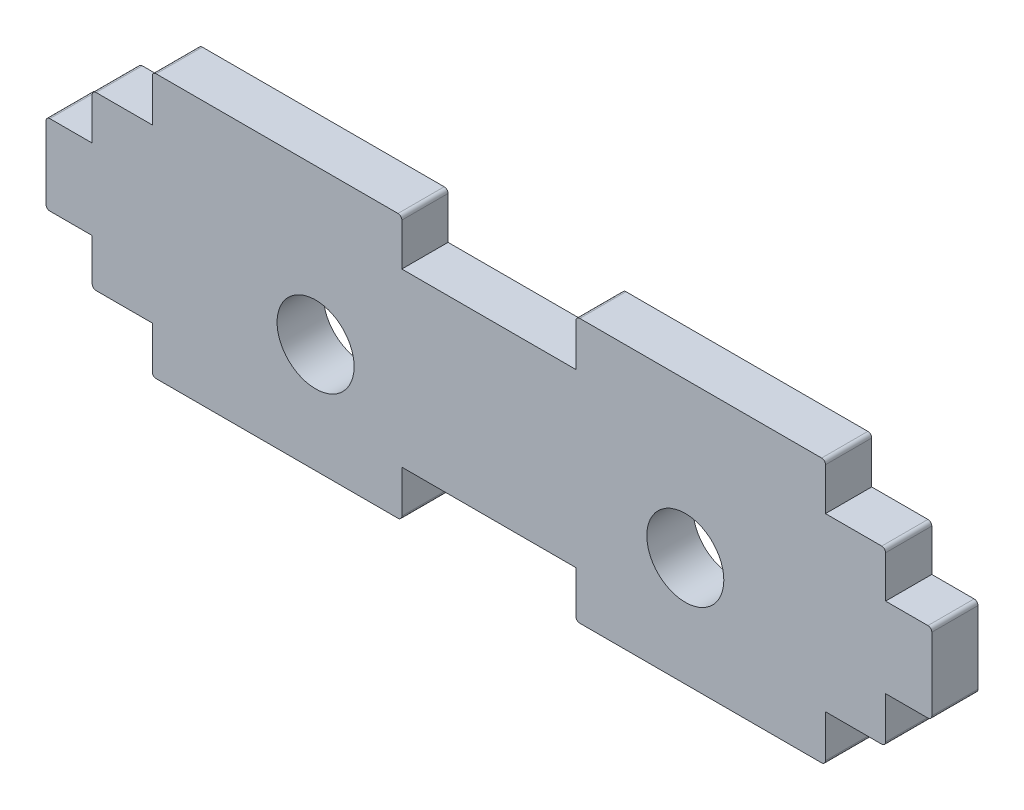
SolidWorks part; units mm, degrees
material "Acrylic (Medium-high impact)"
ref_plane "Front Plane" through (0, 0, 0) normal (0, 0, 1) x (1, 0, 0)
ref_plane "Top Plane" through (0, 0, 0) normal (0, 1, 0) x (1, 0, 0)
ref_plane "Right Plane" through (0, 0, 0) normal (1, 0, 0) x (0, 0, -1)
sketch "Sketch2" plane through (0, 0, 0) normal (0, 0, 1) x (1, 0, 0)
  line L0 (34.25, 2.0562) -> (49.95, 2.0562)
  line L1 (6.75, 2.0562) -> (22.45, 2.0562)
  line L2 (-0.4, 8.275) -> (-0.4, 12.975)
  line L3 (6.75, 19.1937) -> (22.45, 19.1937)
  line L4 (57.1, 8.275) -> (57.1, 12.975)
  line L5 (2.85, 5.0562) -> (6.5, 5.0562)
  line L8 (50.2, 5.0562) -> (53.85, 5.0562)
  line L10 (34.25, 19.1937) -> (49.95, 19.1937)
  line L11 (2.85, 16.1937) -> (6.5, 16.1937)
  line L12 (2.6, 13.225) -> (2.6, 15.9437)
  line L14 (6.5, 2.3062) -> (6.5, 5.0562)
  line L16 (22.7, 2.3062) -> (22.7, 5.0562)
  line L17 (22.7, 5.0562) -> (34, 5.0562)
  line L18 (50.2, 5.0562) -> (50.2, 2.3062)
  line L20 (34, 5.0562) -> (34, 2.3062)
  line L21 (50.2, 16.1937) -> (53.85, 16.1937)
  line L22 (6.5, 16.1937) -> (6.5, 18.9437)
  line L24 (22.7, 16.1937) -> (22.7, 18.9437)
  line L26 (34, 18.9437) -> (34, 16.1937)
  line L27 (-0.15, 13.225) -> (2.6, 13.225)
  line L28 (50.2, 18.9437) -> (50.2, 16.1937)
  line L29 (22.7, 16.1937) -> (34, 16.1937)
  line L31 (-0.15, 8.025) -> (2.6, 8.025)
  line L32 (54.1, 13.225) -> (54.1, 15.9437)
  line L33 (2.6, 8.025) -> (2.6, 5.3062)
  line L34 (56.85, 13.225) -> (54.1, 13.225)
  line L36 (56.85, 8.025) -> (54.1, 8.025)
  line L38 (54.1, 8.025) -> (54.1, 5.3062)
  arc A0 (6.75, 19.1937) -> (6.5, 18.9437) centre (6.75, 18.9437) ccw
  arc A1 (22.7, 18.9437) -> (22.45, 19.1937) centre (22.45, 18.9437) ccw
  arc A2 (34.25, 19.1937) -> (34, 18.9437) centre (34.25, 18.9437) ccw
  arc A3 (50.2, 18.9437) -> (49.95, 19.1937) centre (49.95, 18.9437) ccw
  arc A4 (57.1, 12.975) -> (56.85, 13.225) centre (56.85, 12.975) ccw
  arc A5 (56.85, 8.025) -> (57.1, 8.275) centre (56.85, 8.275) ccw
  arc A6 (49.95, 2.0562) -> (50.2, 2.3062) centre (49.95, 2.3062) ccw
  arc A7 (34, 2.3062) -> (34.25, 2.0562) centre (34.25, 2.3062) ccw
  arc A8 (22.45, 2.0562) -> (22.7, 2.3062) centre (22.45, 2.3062) ccw
  arc A9 (6.5, 2.3062) -> (6.75, 2.0562) centre (6.75, 2.3062) ccw
  arc A10 (-0.4, 8.275) -> (-0.15, 8.025) centre (-0.15, 8.275) ccw
  arc A11 (-0.15, 13.225) -> (-0.4, 12.975) centre (-0.15, 12.975) ccw
  circle A12 centre (17.1, 9.1562) radius 2.5
  circle A13 centre (41.1, 9.1562) radius 2.5
  arc A14 (2.6, 5.3062) -> (2.85, 5.0562) centre (2.85, 5.3062) ccw
  arc A15 (2.85, 16.1937) -> (2.6, 15.9437) centre (2.85, 15.9437) ccw
  arc A16 (54.1, 15.9437) -> (53.85, 16.1937) centre (53.85, 15.9437) ccw
  arc A17 (53.85, 5.0562) -> (54.1, 5.3062) centre (53.85, 5.3062) ccw
  dimension "D19" = 0.5
  dimension "D24" = 0.5
  dimension "D27" = 0.5
  dimension "D30" = 0.5
  dimension "D33" = 0.5
  dimension "D44" = 0.5
  dimension "D45" = 0.5
  dimension "D46" = 0.5
  dimension "D47" = 0.5
  dimension "D48" = 0.5
  dimension "D51" = 0.5
  dimension "D54" = 0.5
  dimension "D16" = 5
  dimension "D56" = 5
  dimension "D67" = 0.5
  dimension "D70" = 0.5
  dimension "D73" = 0.5
  dimension "D76" = 0.5
  dimension "D1" = 5.2
  dimension "D3" = 3
  dimension "D4" = 3
  dimension "D6" = 6.9
  dimension "D7" = 6.9
  dimension "D8" = 17.1375
  dimension "D9" = 2.9688
  dimension "D10" = 2.9688
  dimension "D11" = 4.1
  dimension "D12" = 5.2
  dimension "D13" = 57.5
  dimension "D14" = 6.9
  dimension "D15" = 14.5
  dimension "D17" = 6.9
  dimension "D18" = 3
  dimension "D20" = 0.25
  dimension "D21" = 0.25
  dimension "D22" = 0.25
  dimension "D23" = 0.25
  dimension "D25" = 0.25
  dimension "D26" = 0.25
  dimension "D28" = 0.25
  dimension "D29" = 0.25
  dimension "D31" = 0.25
  dimension "D32" = 0.25
  dimension "D34" = 0.25
  dimension "D35" = 0.25
  dimension "D36" = 0.25
  dimension "D37" = 0.25
  dimension "D38" = 0.25
  dimension "D39" = 0.25
  dimension "D40" = 0.25
  dimension "D41" = 0.25
  dimension "D42" = 0.25
  dimension "D43" = 0.25
  dimension "D49" = 0.25
  dimension "D50" = 0.25
  dimension "D52" = 0.25
  dimension "D53" = 0.25
  dimension "D55" = 4.1
  dimension "D57" = 3
  dimension "D58" = 38.5
  dimension "D59" = 16.2
  dimension "D60" = 16.2
  dimension "D61" = 16.2
  dimension "D62" = 16.2
  dimension "D63" = 3
  dimension "D64" = 3
  dimension "D65" = 0.25
  dimension "D66" = 0.25
  dimension "D68" = 0.25
  dimension "D69" = 0.25
  dimension "D71" = 0.25
  dimension "D72" = 0.25
  dimension "D74" = 0.25
  dimension "D75" = 0.25
extrude "Boss-Extrude1" add sketch "Sketch2" along normal blind 3
